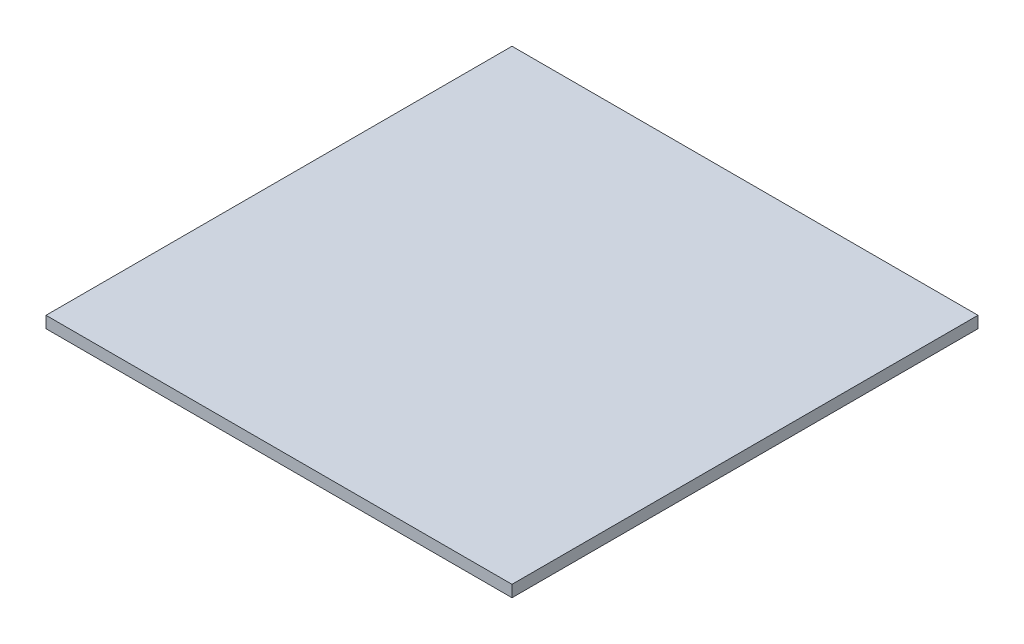
SolidWorks part; units mm, degrees
ref_plane "Front Plane" through (0, 0, 0) normal (0, 0, 1) x (1, 0, 0)
ref_plane "Top Plane" through (0, 0, 0) normal (0, 1, 0) x (1, 0, 0)
ref_plane "Right Plane" through (0, 0, 0) normal (1, 0, 0) x (0, 0, -1)
sketch "Sketch1" plane through (0, 0, 0) normal (0, 1, 0) x (1, 0, 0)
  line L1 (-200, -200) -> (200, -200)
  line L2 (-200, -200) -> (-200, 200)
  line L3 (-200, 200) -> (200, 200)
  line L4 (200, -200) -> (200, 200)
  line L5 (-200, -200) -> (200, 200) construction
  line L6 (-200, 200) -> (200, -200) construction
  point P0 (0, 0)
  dimension "D1" = 400
  dimension "D2" = 400
extrude "Boss-Extrude1" add sketch "Sketch1" against normal blind 10
